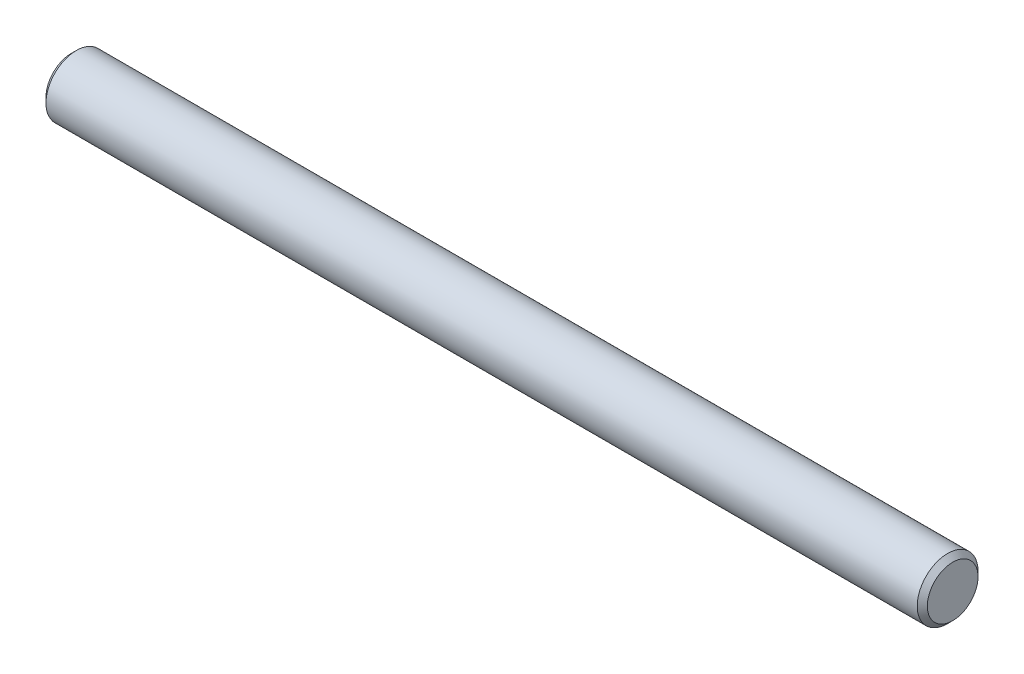
SolidWorks part; units mm, degrees
material "Chrome Stainless Steel"
ref_plane "Front Plane" through (0, 0, 0) normal (0, 0, 1) x (1, 0, 0)
ref_plane "Top Plane" through (0, 0, 0) normal (0, 1, 0) x (1, 0, 0)
ref_plane "Right Plane" through (0, 0, 0) normal (1, 0, 0) x (0, 0, -1)
sketch "Sketch1" plane through (0, 0, 0) normal (1, 0, 0) x (0, 0, -1)
  circle A0 centre (0, 0) radius 6
  dimension "D1" = 12
extrude "Boss-Extrude1" add sketch "Sketch1" along normal blind 174
chamfer "Chamfer1" distance 1 angle 45 2 edges at (174, 0, -6) (0, 0, -6)
